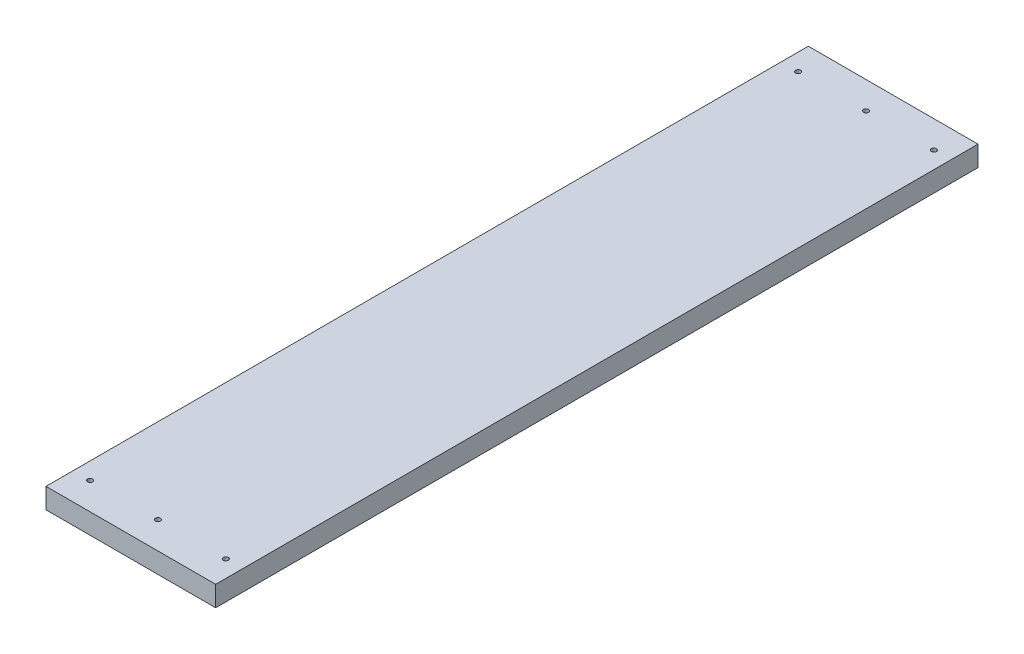
SolidWorks part; units mm, degrees
ref_plane "Front Plane" through (0, 0, 0) normal (0, 0, 1) x (1, 0, 0)
ref_plane "Top Plane" through (0, 0, 0) normal (0, 1, 0) x (1, 0, 0)
ref_plane "Right Plane" through (0, 0, 0) normal (1, 0, 0) x (0, 0, -1)
other "Bounding Box"
ref_plane "Default Plane" through (75, 9, -337) normal (-1, 0, 0) x (0, 0, 1)
sketch "Sketch1" plane through (0, 0, 0) normal (0, 1, 0) x (1, 0, 0)
  line L0 (-75, 337) -> (75, -337) construction
  line L1 (-75, 337) -> (75, 337)
  line L2 (-75, 337) -> (-75, -337)
  line L3 (-75, -337) -> (75, -337)
  line L4 (75, 337) -> (75, -337)
  line L5 (75, 337) -> (-75, -337) construction
  point P0 (0, 0)
  dimension "D1" = 150
  dimension "D2" = 674
extrude "Boss-Extrude1" add sketch "Sketch1" along normal mid plane 18 contours L4 L3 L2 L1
hole_wizard "CSK for #8 Flat Head Machine Screw (100)1" positions "Sketch2" profile "Sketch3" countersink size "#8" standard "ANSI Inch" end condition through all
sketch "Sketch2" plane through (-75, -9, 0) normal (0, -1, 0) x (0, 0, -1)
  line L1 (-313, 135) -> (-313, 15) construction
  line L2 (-305, 18.2728) -> (-305, 21.7272) construction
  line L3 (-321, 21.7272) -> (-321, 18.2728) construction
  point P0 (-313, 135)
  point P9 (-313, 75)
  point P14 (-313, 15)
sketch "Sketch3" plane through (60, -9, 313) normal (1, 0, 0) x (0, 0, -1)
  line L0 (0, 0) -> (0, 18)
  line L1 (0, 18) -> (2.2479, 18)
  line L2 (2.2479, 18) -> (2.2479, 1.6518)
  line L3 (2.2479, 1.6518) -> (4.2164, 0)
  line L5 (4.2164, 0) -> (0, 0)
  line L6 (-2.2479, 1.6518) -> (-4.2164, 0) construction
  line L11 (0, -6.35) -> (0, 107.95) construction
  dimension "Thru Hole Dia." = 4.4958
  dimension "Thru Hole Depth" = 18
  dimension "Near C'Sink Dia." = 8.4328
  dimension "Near C'Sink Angle" = 100
hole_wizard "#8-36 Tapped Hole1" positions "Sketch6" profile "Sketch5" tap size "#8-36" standard "ANSI Inch"
sketch "Sketch6" plane through (-75, 0, 0) normal (-1, 0, 0) x (0, 0, 1)
  line L0 (249, 0) -> (225, 0) construction
  line L2 (337, 9) -> (337, -9) construction
  line L3 (-337, -9) -> (337, -9) construction
  line L4 (-337, 9) -> (337, 9) construction
  point P0 (249, 0)
  point P2 (225, 0)
  point P8 (237, 0)
  dimension "D1" = 100
  dimension "D2" = 24
sketch "Sketch5" plane through (-75, 0, 249) normal (0, 1, 0) x (0, 0, 1)
  line L0 (0, 0) -> (0, 26.0378)
  line L1 (0, 26.0378) -> (1.7272, 25)
  line L2 (1.7272, 25) -> (1.7272, 0)
  line L5 (1.7272, 0) -> (0, 0)
  line L10 (0, 26.0378) -> (-1.7272, 25) construction
  line L11 (0, -6.35) -> (0, 107.95) construction
  dimension "Tap Drill Dia." = 3.4544
  dimension "Tap Drill Depth" = 25
  dimension "Drill Angle" = 118
cosmetic thread "Hole Thread1"
cosmetic thread "Hole Thread2"
mirror "Mirror1" about plane through (0, 0, 0) normal (0, 0, 1) of "#8-36 Tapped Hole1", "CSK for #8 Flat Head Machine Screw (100)1"
cosmetic thread "Hole Thread3"
cosmetic thread "Hole Thread4"
